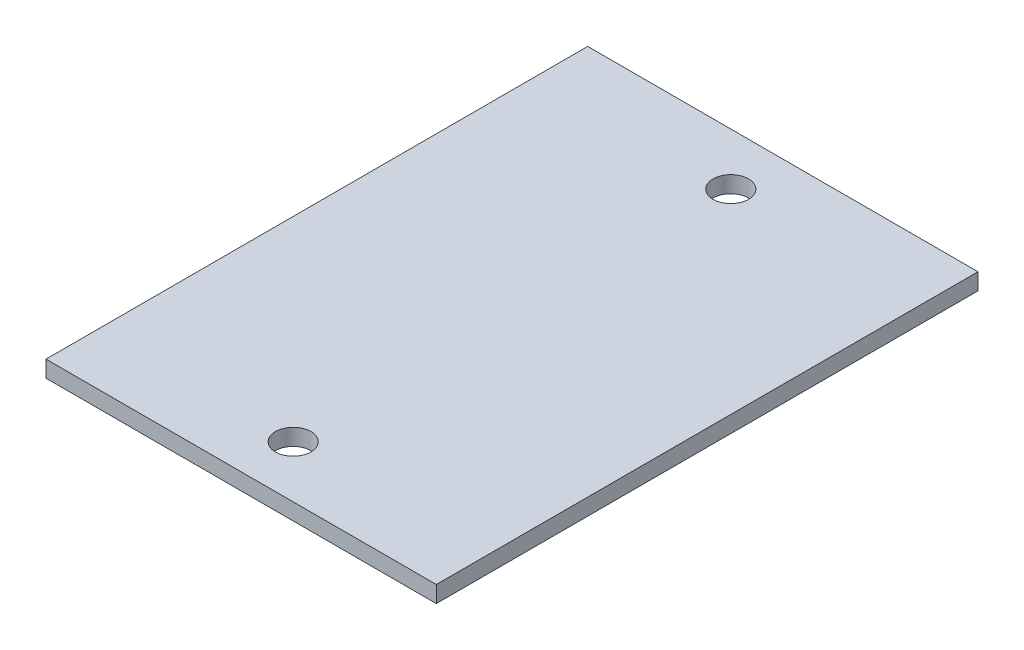
SolidWorks part; units mm, degrees
ref_plane "Front Plane" through (0, 0, 0) normal (0, 0, 1) x (1, 0, 0)
ref_plane "Top Plane" through (0, 0, 0) normal (0, 1, 0) x (1, 0, 0)
ref_plane "Right Plane" through (0, 0, 0) normal (1, 0, 0) x (0, 0, -1)
sketch "Sketch1" plane through (0, 0, 0) normal (0, 1, 0) x (1, 0, 0)
  line L0 (0, 0) -> (0, 50000) construction
  line L1 (-16.5, -22.9) -> (16.5, -22.9)
  line L2 (-16.5, -22.9) -> (-16.5, 22.9)
  line L3 (-16.5, 22.9) -> (16.5, 22.9)
  line L4 (16.5, -22.9) -> (16.5, 22.9)
  line L5 (-16.5, -22.9) -> (16.5, 22.9) construction
  line L6 (-16.5, 22.9) -> (16.5, -22.9) construction
  circle A0 centre (0, 18.5) radius 1.5
  circle A1 centre (0, -18.5) radius 1.5
  point P0 (0, 0)
  dimension "D3" = 37
  dimension "D1" = 45.8
  dimension "D2" = 33
  dimension "D4" = 4.4
extrude "Boss-Extrude1" add sketch "Sketch1" along normal blind 1.4
